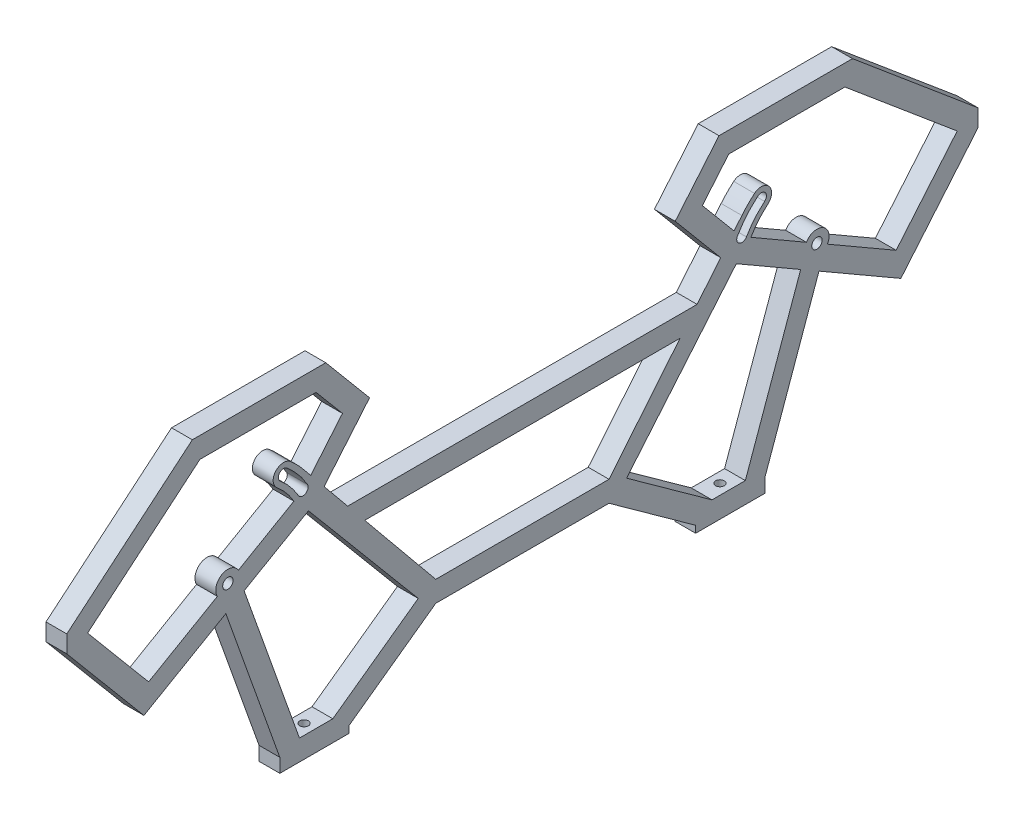
SolidWorks part; units mm, degrees
material "1060 Alloy"
ref_plane "Front Plane" through (0, 0, 0) normal (0, 0, 1) x (1, 0, 0)
ref_plane "Top Plane" through (0, 0, 0) normal (0, 1, 0) x (1, 0, 0)
ref_plane "Right Plane" through (0, 0, 0) normal (1, 0, 0) x (0, 0, -1)
sketch "Sketch1" plane through (0, 0, 0) normal (1, 0, 0) x (0, 0, -1)
  line L0 (65.8489, 71.0697) -> (85, 55) construction
  line L1 (50, 0) -> (70, 0)
  line L2 (131.2449, 61.8851) -> (104.8907, 30.4773) construction
  line L3 (131.2449, 61.8851) -> (73.0256, 110.737) construction
  line L4 (104.8907, 30.4773) -> (46.6713, 79.3292) construction
  line L5 (73.0256, 110.737) -> (46.6713, 79.3292) construction
  line L6 (50, 0) -> (50, 2)
  line L7 (50, 2) -> (25, 20)
  line L8 (25, 20) -> (0, 20)
  line L9 (120.803, 46.5093) -> (61.0516, 96.6468) construction
  line L10 (0, 20) -> (0, 26)
  line L11 (0, 26) -> (25, 26)
  line L12 (25, 26) -> (45.5054, 51)
  line L13 (45.5054, 51) -> (0, 51)
  line L14 (65.0961, 75.6176) -> (85.3963, 58.5837) construction
  line L15 (65.0961, 75.6176) -> (82.13, 95.9178) construction
  line L16 (85.3963, 58.5837) -> (102.4301, 78.8839) construction
  line L17 (0, 51) -> (0, 57)
  line L18 (82.13, 95.9178) -> (102.4301, 78.8839) construction
  line L19 (0, 57) -> (50.4267, 57)
  line L20 (106.773, 98) -> (-82.0096, 98) construction
  line L21 (44.0994, 80.9313) -> (57.2251, 65.2887)
  line L22 (68.9303, 74.1511) -> (85, 55) construction
  line L23 (85, 55) -> (63.3494, 67.5) construction
  line L24 (30.0596, 23.7505) -> (61.7373, 61.5025)
  line L25 (61.7373, 61.5025) -> (80.3101, 50.7795)
  line L26 (80.3101, 50.7795) -> (64.3431, 6)
  line L27 (64.3431, 6) -> (54.7131, 6)
  line L28 (54.7131, 6) -> (30.0596, 23.7505)
  line L29 (70, 0) -> (70, 4)
  line L30 (70, 4) -> (85.5926, 47.7296)
  line L31 (85.5926, 47.7296) -> (109.2241, 34.086)
  line L32 (109.2241, 34.086) -> (131.4864, 60.6171)
  line L33 (131.4864, 65.5988) -> (95.2556, 96)
  line L34 (95.2556, 96) -> (56.7435, 96)
  line L35 (132, 92.0287) -> (132, -4.4174) construction
  line L36 (59.5414, 90) -> (51.9319, 80.9313)
  line L37 (140, 92.0287) -> (140, -4.4174) construction
  line L38 (88.0311, 53.25) -> (107.864, 41.7995)
  line L39 (65.9474, 66) -> (81.9689, 56.75)
  line L40 (131.4864, 65.5988) -> (131.4864, 60.6171)
  line L42 (107.864, 41.7995) -> (125.4864, 62.8009)
  line L43 (125.4864, 62.8009) -> (93.0718, 90)
  line L44 (93.0718, 90) -> (59.5414, 90)
  line L46 (56.7435, 96) -> (44.0994, 80.9313)
  line L47 (61.7373, 61.5025) -> (59.4392, 63.4309) construction
  line L48 (59.4392, 63.4309) -> (65.8489, 71.0697) construction
  line L49 (85, 55) -> (75.9689, 29.6723) construction
  line L50 (57.2251, 65.2887) -> (50.4267, 57)
  line L51 (51.9319, 80.9313) -> (61.0968, 70.009)
  line L52 (61.0968, 70.009) -> (63.3508, 72.757)
  circle A0 centre (85, 55) radius 1.5
  circle A1 centre (65.8489, 71.0697) radius 1.5 construction
  circle A2 centre (85, 55) radius 3 construction
  circle A3 centre (65.8489, 71.0697) radius 3 construction
  arc A4 (63.3494, 67.5) -> (68.9303, 74.1511) centre (85, 55) cw construction
  arc A5 (67.9661, 75.3002) -> (62.0503, 68.25) centre (85, 55) ccw
  arc A6 (69.8945, 73.002) -> (64.6484, 66.75) centre (85, 55) ccw
  arc A7 (69.8945, 73.002) -> (67.9661, 75.3002) centre (68.9303, 74.1511) ccw
  arc A8 (62.0503, 68.25) -> (64.6484, 66.75) centre (63.3494, 67.5) ccw
  arc A9 (70.8587, 71.853) -> (65.9474, 66) centre (85, 55) ccw
  arc A10 (63.3508, 72.757) -> (67.0019, 76.4492) centre (85, 55) cw
  arc A11 (67.0019, 76.4492) -> (70.8587, 71.853) centre (68.9303, 74.1511) cw
  arc A12 (81.9689, 56.75) -> (88.0311, 53.25) centre (85, 55) cw
  point P25 (65.8489, 71.0697)
  dimension "D14" = 3
  dimension "D16" = 1.5
  dimension "D21" = 1.5
  dimension "D29" = 6
  dimension "D30" = 1.5
  dimension "D19" = 3.5
  dimension "D1" = 6
  dimension "D2" = 31
  dimension "D3" = 3
  dimension "D4" = 41
  dimension "D5" = 20
  dimension "D6" = 55
  dimension "D7" = 85
  dimension "D8" = 25
  dimension "D9" = 20
  dimension "D10" = 40
  dimension "D11" = 50
  dimension "D12" = 26.5
  dimension "D13" = 26.5
  dimension "D15" = 3.5
  dimension "D17" = 10
  dimension "D18" = 6
  dimension "D20" = 132
  dimension "D22" = 3
  dimension "D23" = 3
  dimension "D24" = 140
  dimension "D25" = 1
  dimension "D26" = 3
  dimension "D27" = 2
  dimension "D28" = 98
  dimension "D31" = 6
  dimension "D32" = 6
  dimension "D33" = 6
  dimension "D34" = 6
  dimension "D35" = 6
  dimension "D36" = 6
  dimension "D37" = 3
  dimension "D38" = 6
  dimension "D39" = 6
  dimension "D40" = 20
  dimension "D41" = 6
  dimension "D42" = 25
  dimension "D43" = 6
  dimension "D44" = 2
  dimension "D45" = 4
  dimension "D46" = 25
  dimension "D47" = 6
extrude "Boss-Extrude1" add sketch "Sketch1" along normal blind 6
hole_wizard "Tap Drill for M3 Tap1" positions "Sketch3" profile "Sketch2" hole size "M3" standard "ISO"
sketch "Sketch3" plane through (0, 0, 0) normal (0, -1, 0) x (-1, 0, 0)
  line L1 (-6, 50) -> (-6, 70) construction
  line L2 (-6, 70) -> (0, 70) construction
  point P0 (-3, 60)
  dimension "D1" = 10
  dimension "D2" = 3
sketch "Sketch2" plane through (3, 0, -60) normal (1, 0, 0) x (0, 0, -1)
  line L0 (0, 0) -> (0, 10.7511)
  line L1 (0, 10.7511) -> (1.25, 10)
  line L2 (1.25, 10) -> (1.25, 0)
  line L5 (1.25, 0) -> (0, 0)
  line L10 (0, 10.7511) -> (-1.25, 10) construction
  line L11 (0, -6.35) -> (0, 107.95) construction
  dimension "Hole Dia." = 2.5
  dimension "Hole Depth" = 10
  dimension "Drill Angle" = 118
mirror "Mirror1" about plane through (0, 0, 0) normal (0, 0, 1) of "Boss-Extrude1", "Tap Drill for M3 Tap1"
